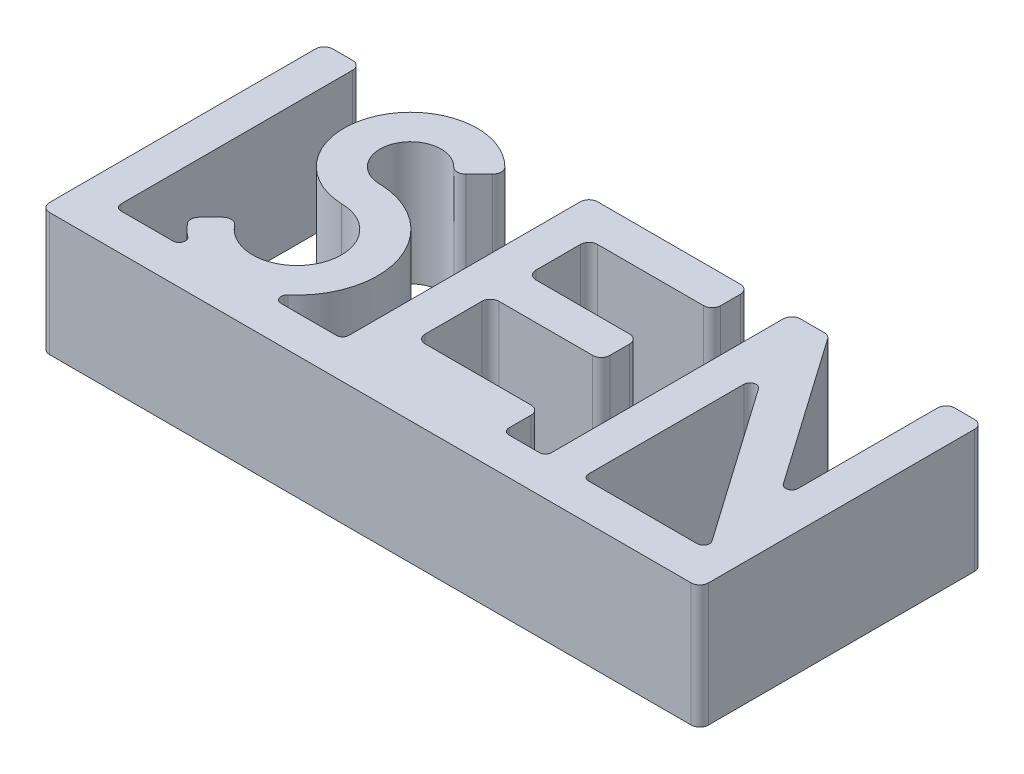
SolidWorks part; units mm, degrees
ref_plane "Plan de face" through (0, 0, 0) normal (0, 0, 1) x (1, 0, 0)
ref_plane "Plan de dessus" through (0, 0, 0) normal (0, 1, 0) x (1, 0, 0)
ref_plane "Plan de droite" through (0, 0, 0) normal (1, 0, 0) x (0, 0, -1)
sketch "Esquisse3" plane through (0, 0, 0) normal (0, 1, 0) x (1, 0, 0)
  line L0 (0, 60.1736) -> (0, -29.9114) construction
  line L1 (-101.6427, 0) -> (66.9583, 0) construction
  line L2 (-96.5415, 24.6604) -> (0, 24.6604) construction
  line L3 (0, 44.6604) -> (-96.5415, 44.6604) construction
  line L4 (-82.4, 43.9604) -> (-82.4, 24.6604)
  line L5 (-79.4, 25.1604) -> (-79.4, 43.9604)
  line L6 (-81.7, 44.6604) -> (-80.1, 44.6604)
  line L8 (-60.9, 25.1604) -> (-60.9, 43.9604)
  line L9 (-60.2, 44.6604) -> (-48.6, 44.6604)
  line L10 (-47.9, 43.9604) -> (-47.9, 42.3604)
  line L11 (-57.9, 46.1261) -> (-57.9, 24.6604) construction
  line L12 (-48.6, 41.6604) -> (-57.2, 41.6604)
  line L13 (-57.9, 40.9604) -> (-57.9, 37.3604)
  line L14 (-57.2, 36.6604) -> (-49.6, 36.6604)
  line L15 (-48.9, 35.9604) -> (-48.9, 34.3604)
  line L16 (-49.6, 33.6604) -> (-57.2, 33.6604)
  line L17 (-57.9, 32.9604) -> (-57.9, 28.3641)
  line L18 (-57.2, 27.6641) -> (-48.6, 27.6641)
  line L19 (-47.9, 26.9641) -> (-47.9, 25.1604)
  line L21 (-44.4297, 25.1604) -> (-44.4297, 43.9604)
  line L22 (-41.4297, 39.3461) -> (-31.1466, 24.6604) construction
  line L23 (-41.4297, 44.6604) -> (-30.5703, 29.1515) construction
  line L24 (-28.9, 24.6604) -> (-28.9, 43.9604)
  line L26 (-32.8086, 32.3482) -> (-41.2207, 44.3619)
  line L27 (-41.7941, 44.6604) -> (-43.7297, 44.6604)
  line L29 (-41.4297, 25.1604) -> (-41.4297, 37.7604)
  line L31 (-31.6975, 25.4471) -> (-40.5201, 38.0471)
  line L32 (-31.5297, 30.5217) -> (-31.5297, 23.1526) construction
  line L33 (-31.2, 44.6604) -> (-29.6, 44.6604)
  line L34 (-70.4675, 31.8563) -> (-70.4675, 24.6604) construction
  line L35 (-68.1507, 30.5217) -> (-78.0524, 30.5217) construction
  line L36 (-68.5418, 39.5373) -> (-72.2711, 39.5373) construction
  line L37 (-65.5929, 43.163) -> (-69.1257, 39.6302) construction
  line L38 (-76.6977, 25.9919) -> (-72.5951, 30.0944) construction
  line L41 (-69.9877, 42.4108) -> (-69.9877, 38.9524) construction
  line L42 (-75.2737, 27.4158) -> (-74.342, 28.3475)
  line L43 (-67.492, 41.2639) -> (-66.4086, 42.3473)
  line L44 (-82.4, 24.6604) -> (-82.4, 22.3604)
  line L45 (-81.7, 21.6604) -> (-29.6, 21.6604)
  line L46 (-28.9, 22.3604) -> (-28.9, 24.6604)
  line L47 (-32.1071, 24.6604) -> (-40.9297, 24.6604)
  line L48 (-44.9297, 24.6604) -> (-47.4, 24.6604)
  line L49 (-31.9, 43.9604) -> (-31.9, 32.6655)
  line L50 (-74.6783, 24.6604) -> (-78.9, 24.6604)
  line L51 (-65.9, 24.6604) -> (-61.4, 24.6604)
  arc A0 (-70.175, 37.0583) -> (-68.4879, 41.2699) centre (-70.263, 39.5373) cw
  arc A1 (-70.457, 34.1281) -> (-66.4046, 43.3332) centre (-70.263, 39.5373) cw
  arc A2 (-70.457, 34.1281) -> (-73.2977, 28.2864) centre (-70.4675, 30.5217) cw
  arc A5 (-70.175, 37.0583) -> (-66.2243, 25.541) centre (-70.4675, 30.5217) cw
  arc A6 (-75.316, 26.4721) -> (-74.3694, 25.5536) centre (-70.4675, 30.5217) ccw
  arc A7 (-60.9, 43.9604) -> (-60.2, 44.6604) centre (-60.2, 43.9604) cw
  arc A8 (-28.9, 43.9604) -> (-29.6, 44.6604) centre (-29.6, 43.9604) ccw
  arc A9 (-31.9, 43.9604) -> (-31.2, 44.6604) centre (-31.2, 43.9604) cw
  arc A10 (-41.7941, 44.6604) -> (-41.2207, 44.3619) centre (-41.7941, 43.9604) cw
  arc A11 (-44.4297, 43.9604) -> (-43.7297, 44.6604) centre (-43.7297, 43.9604) cw
  arc A12 (-75.316, 26.4721) -> (-75.2737, 27.4158) centre (-74.7788, 26.9208) cw
  arc A13 (-73.2977, 28.2864) -> (-74.342, 28.3475) centre (-73.8471, 27.8525) ccw
  arc A14 (-57.9, 28.3641) -> (-57.2, 27.6641) centre (-57.2, 28.3641) ccw
  arc A15 (-57.2, 33.6604) -> (-57.9, 32.9604) centre (-57.2, 32.9604) ccw
  arc A16 (-48.6, 27.6641) -> (-47.9, 26.9641) centre (-48.6, 26.9641) cw
  arc A17 (-48.9, 34.3604) -> (-49.6, 33.6604) centre (-49.6, 34.3604) cw
  arc A18 (-57.9, 37.3604) -> (-57.2, 36.6604) centre (-57.2, 37.3604) ccw
  arc A19 (-57.2, 41.6604) -> (-57.9, 40.9604) centre (-57.2, 40.9604) ccw
  arc A20 (-49.6, 36.6604) -> (-48.9, 35.9604) centre (-49.6, 35.9604) cw
  arc A21 (-47.9, 42.3604) -> (-48.6, 41.6604) centre (-48.6, 42.3604) cw
  arc A22 (-48.6, 44.6604) -> (-47.9, 43.9604) centre (-48.6, 43.9604) cw
  arc A23 (-68.4879, 41.2699) -> (-67.492, 41.2639) centre (-67.987, 41.7589) ccw
  arc A24 (-66.4046, 43.3332) -> (-66.4086, 42.3473) centre (-66.9036, 42.8423) cw
  arc A25 (-79.4, 43.9604) -> (-80.1, 44.6604) centre (-80.1, 43.9604) ccw
  arc A26 (-82.4, 43.9604) -> (-81.7, 44.6604) centre (-81.7, 43.9604) cw
  arc A27 (-40.5201, 38.0471) -> (-41.4297, 37.7604) centre (-40.9297, 37.7604) ccw
  arc A28 (-31.9, 32.6655) -> (-32.8086, 32.3482) centre (-32.3991, 32.635) cw
  arc A29 (-31.6975, 25.4471) -> (-32.1071, 24.6604) centre (-32.1071, 25.1604) cw
  arc A30 (-44.4297, 25.1604) -> (-44.9297, 24.6604) centre (-44.9297, 25.1604) cw
  arc A31 (-40.9297, 24.6604) -> (-41.4297, 25.1604) centre (-40.9297, 25.1604) cw
  arc A32 (-47.9, 25.1604) -> (-47.4, 24.6604) centre (-47.4, 25.1604) ccw
  arc A33 (-60.9, 25.1604) -> (-61.4, 24.6604) centre (-61.4, 25.1604) cw
  arc A34 (-66.2243, 25.541) -> (-65.9, 24.6604) centre (-65.9, 25.1604) ccw
  arc A35 (-74.3694, 25.5536) -> (-74.6783, 24.6604) centre (-74.6783, 25.1604) cw
  arc A36 (-79.4, 25.1604) -> (-78.9, 24.6604) centre (-78.9, 25.1604) ccw
  arc A37 (-29.6, 21.6604) -> (-28.9, 22.3604) centre (-29.6, 22.3604) ccw
  arc A38 (-82.4, 22.3604) -> (-81.7, 21.6604) centre (-81.7, 22.3604) ccw
  point P61 (0, 0)
  point P62 (0, 0)
  point P67 (-60.9, 44.6604)
  point P70 (-28.9, 44.6604)
  point P73 (-31.9, 44.6604)
  point P79 (-44.4297, 44.6604)
  point P82 (-75.703, 26.9866)
  point P85 (-73.722, 28.9676)
  point P88 (-57.9, 27.6641)
  point P91 (-57.9, 33.6604)
  point P98 (-57.9, 36.6604)
  point P101 (-57.9, 41.6604)
  point P108 (-47.9, 44.6604)
  point P111 (-68.0664, 40.6895)
  point P114 (-65.9493, 42.8066)
  point P117 (-79.4, 44.6604)
  point P120 (-82.4, 44.6604)
  point P132 (-44.4297, 24.6604)
  point P135 (-41.4297, 24.6604)
  point P138 (-47.9, 24.6604)
  point P141 (-60.9, 24.6604)
  point P144 (-67.5593, 24.6604)
  point P147 (-68.1113, 24.6604)
  point P150 (-79.4, 24.6604)
  point P155 (0, 0)
  point P156 (0, 0)
  dimension "D23" = 5.1231
  dimension "D29" = 18.5
  dimension "D26" = 9.4123
  dimension "D27" = 2.4805
  dimension "D32" = 0.5
  dimension "D33" = 5.4126
  dimension "D34" = 3
  dimension "D4" = 0.7
  dimension "D19" = 0.5
  dimension "D20" = 0.7
  dimension "D30" = 8.9325
  dimension "D31" = 3.6065
  dimension "D1" = 35
  dimension "D2" = 35
  dimension "D5" = 3
  dimension "D6" = 3
  dimension "D7" = 3
  dimension "D8" = 3
  dimension "D9" = 3
  dimension "D10" = 20
  dimension "D11" = 35
  dimension "D12" = 12.6
  dimension "D13" = 3
  dimension "D14" = 10
  dimension "D15" = 10
  dimension "D16" = 9
  dimension "D17" = 5
  dimension "D18" = 3.0481
  dimension "D21" = 45
  dimension "D22" = 45
  dimension "D24" = 24.6604
  dimension "D25" = 28.9
  dimension "D35" = 3.0037
  dimension "D36" = 1.3176
extrude "Boss.-Extru.1" add sketch "Esquisse3" along normal blind 10
